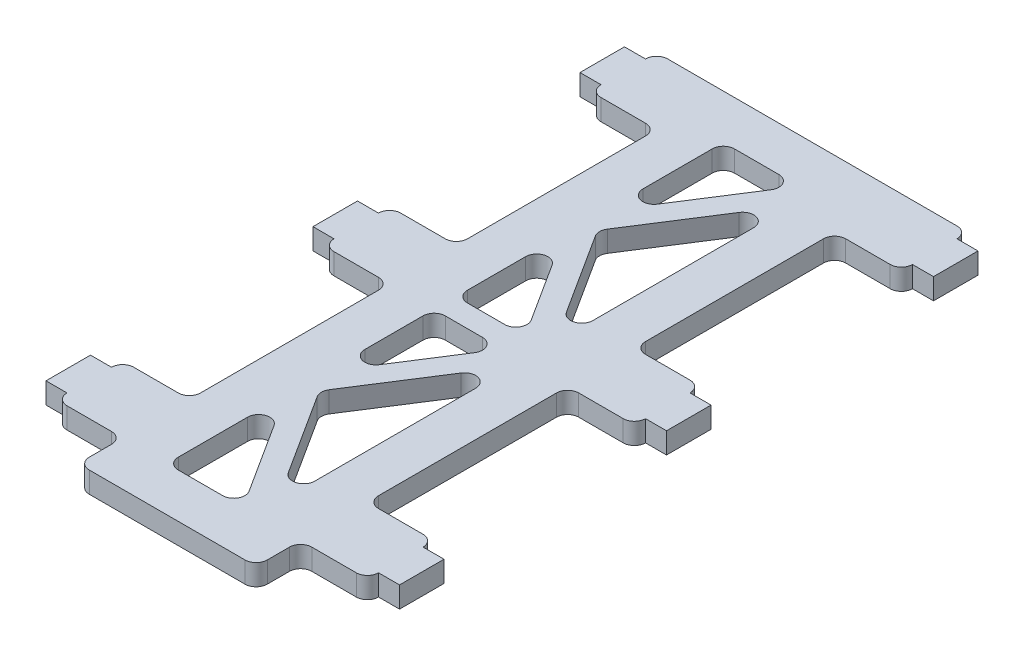
SolidWorks part; units mm, degrees
ref_plane "Front Plane" through (0, 0, 0) normal (0, 0, 1) x (1, 0, 0)
ref_plane "Top Plane" through (0, 0, 0) normal (0, 1, 0) x (1, 0, 0)
ref_plane "Right Plane" through (0, 0, 0) normal (1, 0, 0) x (0, 0, -1)
sketch "Sketch1" plane through (0, 34.29, 0) normal (0, 1, 0) x (1, 0, 0)
  line L0 (16.0528, 180.975) -> (19.05, 180.975) construction
  line L1 (0, -190.5) -> (0, 187.198) construction
  line L2 (38.1028, 187.198) -> (35.1028, 187.198) construction
  line L3 (35.1028, -190.5) -> (38.1, -190.5) construction
  line L5 (-12.7, 74.6125) -> (12.7, 74.6125)
  line L6 (-12.7, 74.6125) -> (-12.7, 166.6875)
  line L7 (-12.7, 166.6875) -> (12.7, 166.6875)
  line L8 (12.7, 74.6125) -> (12.7, 166.6875)
  line L9 (-12.7, 74.6125) -> (12.7, 166.6875) construction
  line L10 (-12.7, 166.6875) -> (12.7, 74.6125) construction
  point P0 (0, 120.65)
  dimension "D1" = 92.075
  dimension "D2" = 25.4
  dimension "D3" = 14.2875
extrude "Boss-Extrude1" add sketch "Sketch1" along normal mid plane 3 contours L7 L8 L5 L6
sketch "Sketch2" plane through (0, 35.79, 0) normal (0, 1, 0) x (1, 0, 0)
  line L0 (0, 166.6875) -> (0, 65.0186) construction
  line L1 (-12.7, 166.6875) -> (12.7, 166.6875) construction
  line L2 (12.7, 123.825) -> (-12.7, 123.825) construction
  line L5 (-22.225, 166.6875) -> (-12.7, 157.1625) construction
  line L6 (22.225, 157.1625) -> (12.7, 157.1625)
  line L7 (22.225, 157.1625) -> (22.225, 166.6875)
  line L8 (22.225, 166.6875) -> (12.7, 166.6875)
  line L9 (12.7, 157.1625) -> (12.7, 166.6875)
  line L10 (22.225, 157.1625) -> (12.7, 166.6875) construction
  line L11 (22.225, 166.6875) -> (12.7, 157.1625) construction
  line L12 (-22.225, 157.1625) -> (-12.7, 166.6875) construction
  line L13 (-12.7, 157.1625) -> (-12.7, 166.6875)
  line L14 (-22.225, 166.6875) -> (-12.7, 166.6875)
  line L15 (-22.225, 157.1625) -> (-22.225, 166.6875)
  line L16 (-22.225, 157.1625) -> (-12.7, 157.1625)
  line L17 (22.225, 119.0625) -> (12.7, 119.0625)
  line L18 (22.225, 119.0625) -> (22.225, 128.5875)
  line L19 (22.225, 128.5875) -> (12.7, 128.5875)
  line L20 (12.7, 119.0625) -> (12.7, 128.5875)
  line L21 (22.225, 119.0625) -> (12.7, 128.5875) construction
  line L22 (22.225, 128.5875) -> (12.7, 119.0625) construction
  line L23 (-12.7, 119.0625) -> (-12.7, 128.5875)
  line L24 (-22.225, 128.5875) -> (-12.7, 128.5875)
  line L25 (-22.225, 119.0625) -> (-22.225, 128.5875)
  line L26 (-22.225, 119.0625) -> (-12.7, 119.0625)
  line L27 (-22.225, 128.5875) -> (-12.7, 119.0625) construction
  line L28 (-22.225, 119.0625) -> (-12.7, 128.5875) construction
  line L29 (22.225, 80.9625) -> (12.7, 80.9625)
  line L30 (22.225, 80.9625) -> (22.225, 90.4875)
  line L31 (22.225, 90.4875) -> (12.7, 90.4875)
  line L32 (12.7, 80.9625) -> (12.7, 90.4875)
  line L33 (22.225, 80.9625) -> (12.7, 90.4875) construction
  line L34 (22.225, 90.4875) -> (12.7, 80.9625) construction
  line L35 (-12.7, 80.9625) -> (-12.7, 90.4875)
  line L36 (-22.225, 90.4875) -> (-12.7, 90.4875)
  line L37 (-22.225, 80.9625) -> (-22.225, 90.4875)
  line L38 (-22.225, 80.9625) -> (-12.7, 80.9625)
  line L39 (-22.225, 90.4875) -> (-12.7, 80.9625) construction
  line L40 (-22.225, 80.9625) -> (-12.7, 90.4875) construction
  point P11 (17.4625, 161.925)
  point P21 (-17.4625, 161.925)
  point P24 (17.4625, 123.825)
  point P33 (-17.4625, 123.825)
  point P34 (17.4625, 85.725)
  point P43 (-17.4625, 85.725)
  dimension "D1" = 9.525
  dimension "D2" = 9.525
  dimension "D4" = 38.1
  dimension "D3" = 3
extrude "Boss-Extrude2" add sketch "Sketch2" against normal up to surface (3 mm away) up to face at (0, 32.79, -120.65)
sketch "Sketch4" plane through (0, 35.79, 0) normal (0, 1, 0) x (1, 0, 0)
  line L0 (12.7, 128.5875) -> (12.7, 157.1625) construction
  line L1 (-6.35, 160.3375) -> (6.35, 160.3375)
  line L2 (-6.35, 160.3375) -> (-6.35, 80.9625)
  line L3 (-6.35, 80.9625) -> (6.35, 80.9625)
  line L4 (6.35, 160.3375) -> (6.35, 80.9625)
  line L5 (-6.35, 160.3375) -> (6.35, 80.9625) construction
  line L6 (-6.35, 80.9625) -> (6.35, 160.3375) construction
  line L7 (-12.7, 128.5875) -> (-12.7, 157.1625) construction
  line L8 (-22.225, 166.6875) -> (22.225, 166.6875) construction
  line L9 (-12.7, 74.6125) -> (12.7, 74.6125) construction
  line L10 (-6.35, 100.8063) -> (6.35, 100.8063) construction
  line L12 (-6.35, 100.8063) -> (6.35, 120.65) construction
  line L13 (6.35, 120.65) -> (-6.35, 140.4938) construction
  line L14 (6.35, 80.9625) -> (-6.35, 100.8063) construction
  line L15 (-6.35, 140.4938) -> (6.35, 140.4938) construction
  line L17 (7.6871, 81.8182) -> (-4.6614, 101.1128)
  line L18 (-6.35, 140.4938) -> (6.35, 160.3375) construction
  line L19 (6.35, 120.65) -> (-6.35, 120.65) construction
  line L20 (-7.6871, 101.662) -> (5.0129, 121.5057)
  line L21 (5.0129, 80.1068) -> (-8.0386, 100.4997)
  line L22 (6.35, 119.0625) -> (-6.35, 119.0625)
  line L23 (5.0129, 119.7943) -> (-8.2348, 140.4938)
  line L24 (-8.2348, 140.4938) -> (5.0129, 161.1932)
  line L25 (-4.6614, 101.1128) -> (7.9026, 160.0063) construction
  line L26 (-5.0129, 99.9505) -> (7.6871, 119.7943)
  line L27 (-6.35, 100.8063) -> (6.35, 160.3375) construction
  line L29 (6.35, 122.2375) -> (-6.35, 122.2375)
  line L30 (-8.0386, 100.4997) -> (4.7974, 160.6687) construction
  line L31 (7.6871, 121.5057) -> (-4.4652, 140.4938)
  line L32 (-4.4652, 140.4938) -> (7.6871, 159.4818)
  point P0 (0, 120.65)
  dimension "D1" = 6.35
  dimension "D2" = 6.35
  dimension "D3" = 6.35
  dimension "D4" = 6.35
  dimension "D7" = 1.5875
  dimension "D8" = 1.5875
  dimension "D9" = 1.5875
  dimension "D10" = 1.5875
extrude "Cut-Extrude1" cut sketch "Sketch4" against normal through all contours L3 L21 L2 | L26 L17 L4 | L20 L22 L2 | L29 L23 L2 | L32 L31 L4 | L2 L24 L1
fillet "Fillet1" radius 1.5875 42 edges at (-6.35, 34.29, -97.8613) (6.35, 34.29, -83.9075) (22.225, 34.29, -80.9625) (22.225, 34.29, -90.4875) (12.7, 34.29, -90.4875) (12.7, 34.29, -119.0625) (22.225, 34.29, -119.0625) (22.225, 34.29, -128.5875) (12.7, 34.29, -128.5875) (12.7, 34.29, -157.1625) (22.225, 34.29, -157.1625) (22.225, 34.29, -166.6875) (-22.225, 34.29, -157.1625) (-12.7, 34.29, -157.1625) (-12.7, 34.29, -128.5875) (-22.225, 34.29, -128.5875) (-22.225, 34.29, -119.0625) (-12.7, 34.29, -119.0625) (-12.7, 34.29, -90.4875) (-22.225, 34.29, -90.4875) (4.4652, 34.29, -80.9625) (-22.225, 34.29, -166.6875) (-6.35, 34.29, -137.5488) (3.4492, 34.29, -122.2375) (-6.35, 34.29, -122.2375) (6.35, 34.29, -117.705) (6.35, 34.29, -123.595) (-4.4652, 34.29, -140.4938) (6.35, 34.29, -157.3925) (-6.35, 34.29, -160.3375) (4.4652, 34.29, -160.3375) (-6.35, 34.29, -143.4387) (-6.35, 34.29, -103.7512) (-6.35, 34.29, -119.0625) (3.4492, 34.29, -119.0625) (-6.35, 34.29, -80.9625) (-4.4652, 34.29, -100.8063) (-12.7, 34.29, -74.6125) (12.7, 34.29, -74.6125) (12.7, 34.29, -80.9625) (-22.225, 34.29, -80.9625) (-12.7, 34.29, -80.9625)
sketch "Sketch5" plane through (0, 35.79, 0) normal (0, 1, 0) x (1, 0, 0)
  line L0 (22.225, 158.75) -> (22.225, 165.1) construction
  line L1 (25.225, 158.75) -> (22.225, 158.75)
  line L2 (25.225, 158.75) -> (25.225, 165.1)
  line L3 (25.225, 165.1) -> (22.225, 165.1)
  line L4 (22.225, 158.75) -> (22.225, 165.1)
  line L5 (25.225, 158.75) -> (22.225, 165.1) construction
  line L6 (25.225, 165.1) -> (22.225, 158.75) construction
  line L7 (22.225, 158.75) -> (22.225, 165.1) construction
  line L8 (22.225, 161.925) -> (23.725, 161.925) construction
  line L9 (0, 196.0278) -> (0, 0) construction
  line L10 (-22.225, 161.925) -> (-23.725, 161.925) construction
  line L11 (-25.225, 165.1) -> (-22.225, 158.75) construction
  line L12 (-25.225, 158.75) -> (-22.225, 165.1) construction
  line L13 (-22.225, 158.75) -> (-22.225, 165.1)
  line L14 (-25.225, 165.1) -> (-22.225, 165.1)
  line L15 (-25.225, 158.75) -> (-25.225, 165.1)
  line L16 (-25.225, 158.75) -> (-22.225, 158.75)
  line L17 (25.225, 120.65) -> (22.225, 120.65)
  line L18 (25.225, 120.65) -> (25.225, 127)
  line L19 (25.225, 127) -> (22.225, 127)
  line L20 (22.225, 120.65) -> (22.225, 127)
  line L21 (25.225, 120.65) -> (22.225, 127) construction
  line L22 (25.225, 127) -> (22.225, 120.65) construction
  line L23 (22.225, 123.825) -> (23.725, 123.825) construction
  line L24 (-22.225, 120.65) -> (-22.225, 127)
  line L25 (-25.225, 127) -> (-22.225, 127)
  line L26 (-25.225, 120.65) -> (-25.225, 127)
  line L27 (-25.225, 120.65) -> (-22.225, 120.65)
  line L28 (-22.225, 123.825) -> (-23.725, 123.825) construction
  line L29 (-25.225, 127) -> (-22.225, 120.65) construction
  line L30 (-25.225, 120.65) -> (-22.225, 127) construction
  line L31 (25.225, 82.55) -> (22.225, 82.55)
  line L32 (25.225, 82.55) -> (25.225, 88.9)
  line L33 (25.225, 88.9) -> (22.225, 88.9)
  line L34 (22.225, 82.55) -> (22.225, 88.9)
  line L35 (25.225, 82.55) -> (22.225, 88.9) construction
  line L36 (25.225, 88.9) -> (22.225, 82.55) construction
  line L37 (22.225, 85.725) -> (23.725, 85.725) construction
  line L38 (-22.225, 82.55) -> (-22.225, 88.9)
  line L39 (-25.225, 88.9) -> (-22.225, 88.9)
  line L40 (-25.225, 82.55) -> (-25.225, 88.9)
  line L41 (-25.225, 82.55) -> (-22.225, 82.55)
  line L42 (-22.225, 85.725) -> (-23.725, 85.725) construction
  line L43 (-25.225, 88.9) -> (-22.225, 82.55) construction
  line L44 (-25.225, 82.55) -> (-22.225, 88.9) construction
  line L45 (-23.725, 161.925) -> (-23.725, 123.825) construction
  point P0 (23.725, 161.925)
  point P7 (23.725, 123.825)
  point P21 (-23.725, 161.925)
  point P35 (-23.725, 123.825)
  point P36 (23.725, 85.725)
  point P49 (-23.725, 85.725)
  dimension "D1" = 3
  dimension "D2" = 6.35
  dimension "D4" = 38.1
  dimension "D3" = 3
extrude "Boss-Extrude3" add sketch "Sketch5" against normal up to surface (3 mm away)
